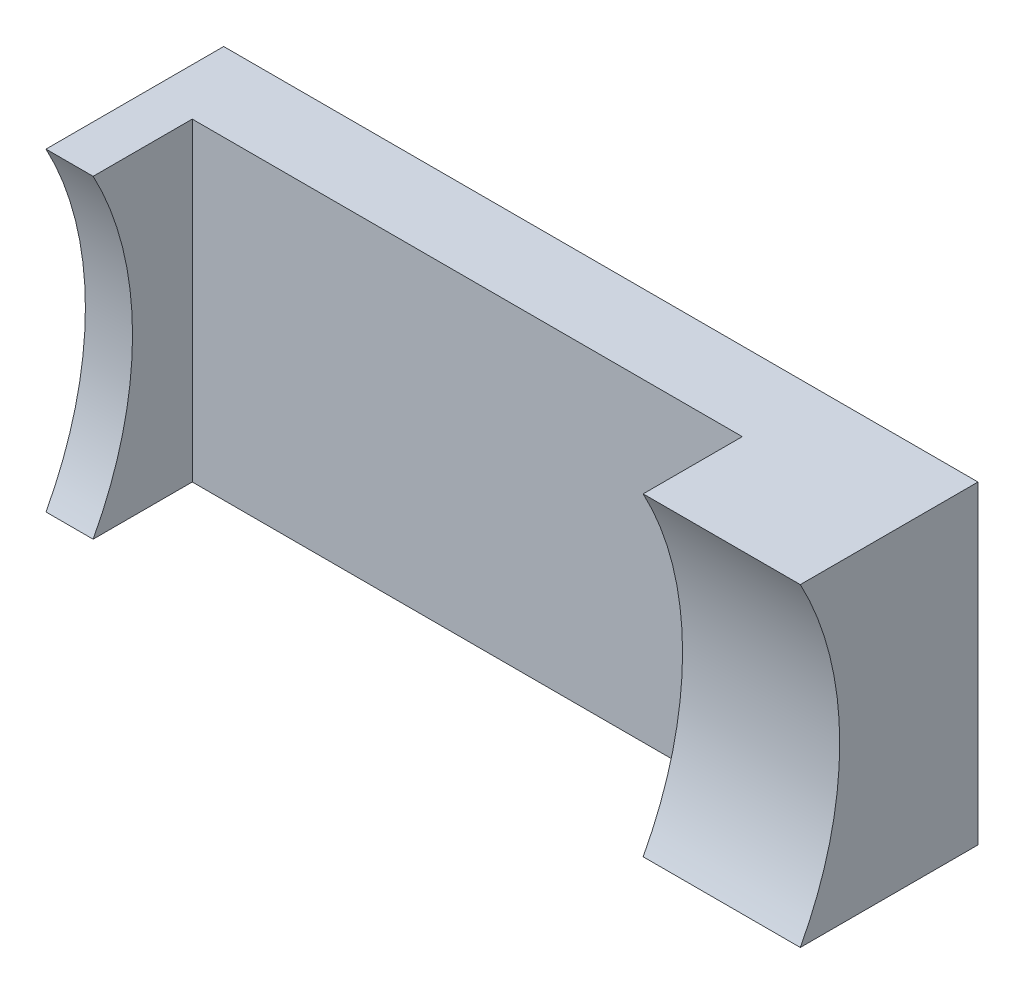
SolidWorks part; units mm, degrees
ref_plane "Piano frontale" through (0, 0, 0) normal (0, 0, 1) x (1, 0, 0)
ref_plane "Piano superiore" through (0, 0, 0) normal (0, 1, 0) x (1, 0, 0)
ref_plane "Piano destro" through (0, 0, 0) normal (1, 0, 0) x (0, 0, -1)
sketch "Schizzo1" plane through (0, 0, 0) normal (0, 0, 1) x (1, 0, 0)
  line L1 (24, -10) -> (-24, -10)
  line L2 (24, -10) -> (24, 10)
  line L3 (24, 10) -> (-24, 10)
  line L4 (-24, -10) -> (-24, 10)
  line L5 (24, -10) -> (-24, 10) construction
  line L6 (24, 10) -> (-24, -10) construction
  point P0 (0, 0)
  dimension "D1" = 20
  dimension "D2" = 48
extrude "Estrusione-Estrusione1" add sketch "Schizzo1" along normal blind 5
sketch "Schizzo2" plane through (0, 0, 5) normal (0, 0, 1) x (1, 0, 0)
  line L0 (-24, -10) -> (24, -10) construction
  line L1 (-24, 10) -> (-21, 10)
  line L2 (-24, 10) -> (-24, -10)
  line L3 (-24, -10) -> (-21, -10)
  line L4 (-21, 10) -> (-21, -10)
  line L6 (24, 10) -> (14, 10)
  line L7 (24, 10) -> (24, -10)
  line L8 (24, -10) -> (14, -10)
  line L9 (14, 10) -> (14, -10)
  dimension "D1" = 3
  dimension "D2" = 10
extrude "Estrusione-Estrusione2" add sketch "Schizzo2" along normal blind 25
sketch "Schizzo3" plane through (-24, 0, 0) normal (-1, 0, 0) x (0, 0, 1)
  line L0 (0, 0) -> (30, 0) construction
  line L1 (30, 10) -> (30, -10) construction
  circle A0 centre (30, 0) radius 21.2
  dimension "D1" = 42.4
extrude "Taglio-Estrusione1" cut sketch "Schizzo3" against normal up to surface (48 mm away) up to face at (24, 0, 15)
sketch "Schizzo4" plane through (0, 0, 0) normal (0, 0, -1) x (-1, 0, 0)
  line L0 (-14.7252, 0) -> (19.787, 0) construction
  line L2 (-24, -10) -> (-24, 10) construction
  circle A0 centre (-9, 0) radius 2.5
  circle A1 centre (11, 0) radius 2.5
  dimension "D1" = 5
  dimension "D2" = 5
  dimension "D3" = 20
  dimension "D4" = 15
extrude "Estrusione-Estrusione3" add sketch "Schizzo4" along normal blind 5
